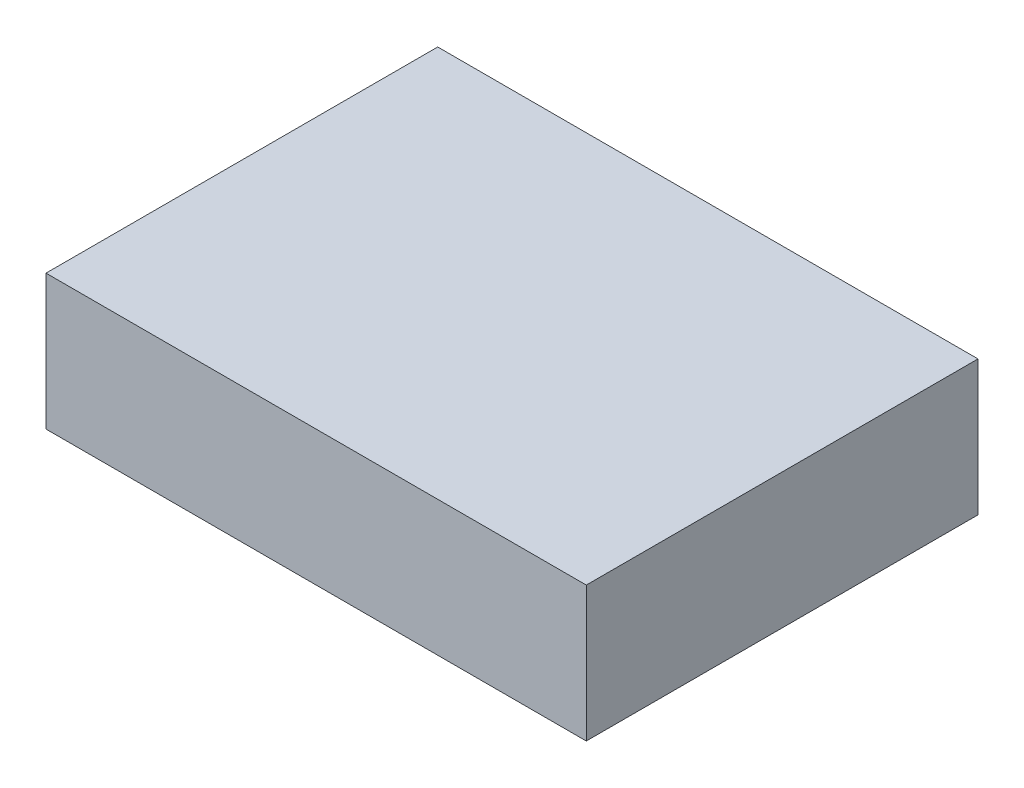
SolidWorks part; units mm, degrees
ref_plane "Front Plane" through (0, 0, 0) normal (0, 0, 1) x (1, 0, 0)
ref_plane "Top Plane" through (0, 0, 0) normal (0, 1, 0) x (1, 0, 0)
ref_plane "Right Plane" through (0, 0, 0) normal (1, 0, 0) x (0, 0, -1)
sketch "Sketch1" plane through (0, 0, 0) normal (0, 1, 0) x (1, 0, 0)
  line L1 (0, 0) -> (40, 0)
  line L2 (0, 0) -> (0, 29)
  line L3 (0, 29) -> (40, 29)
  line L4 (40, 0) -> (40, 29)
extrude "Boss-Extrude1" add sketch "Sketch1" along normal blind 10
